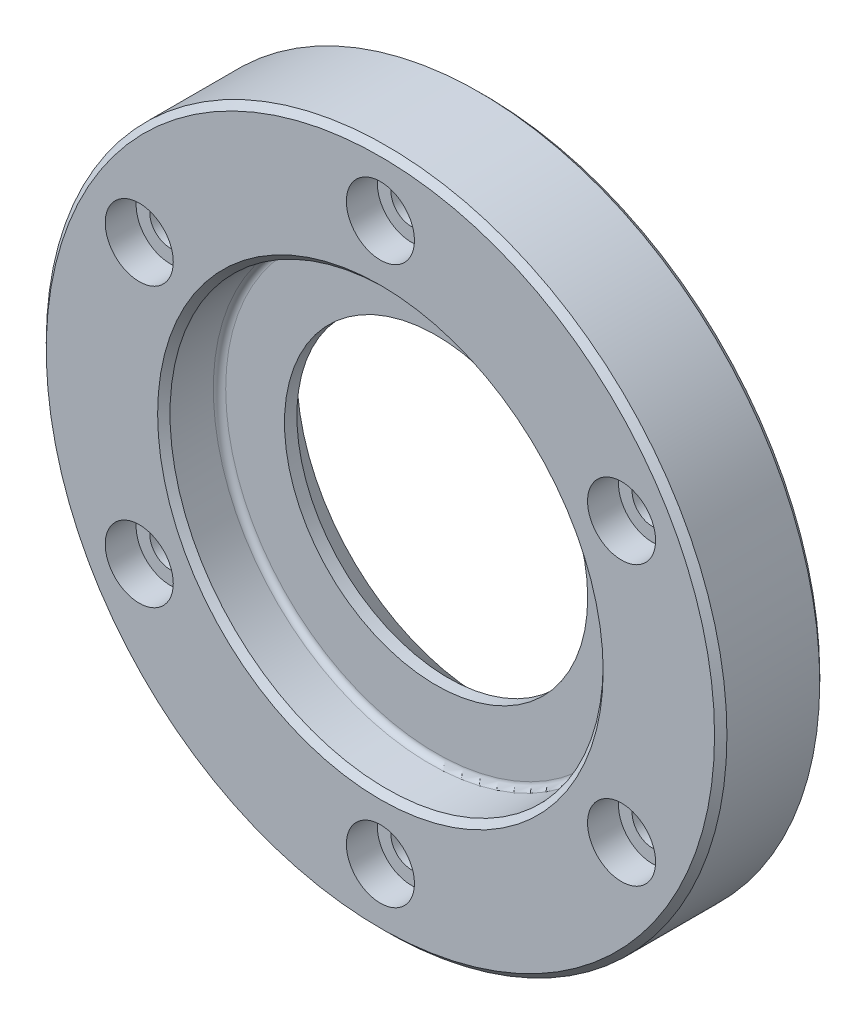
SolidWorks part; units mm, degrees
ref_plane "Front Plane" through (0, 0, 0) normal (0, 0, 1) x (1, 0, 0)
ref_plane "Top Plane" through (0, 0, 0) normal (0, 1, 0) x (1, 0, 0)
ref_plane "Right Plane" through (0, 0, 0) normal (1, 0, 0) x (0, 0, -1)
sketch "Sketch1" plane through (0, 0, 0) normal (1, 0, 0) x (0, 0, -1)
  line L0 (9, 24.5) -> (11, 24.5)
  line L1 (17, 30.5) -> (17, 54)
  line L2 (16, 55) -> (1, 55)
  line L3 (0, 54) -> (0, 36)
  line L4 (1, 35) -> (8, 35)
  line L5 (9, 34) -> (9, 24.5)
  line L6 (11, 24.5) -> (17, 30.5)
  line L7 (0, 0) -> (42.912, 0) construction
  line L8 (17, 54) -> (16, 55)
  line L9 (1, 55) -> (0, 54)
  line L10 (0, 36) -> (1, 35)
  arc A0 (8, 35) -> (9, 34) centre (8, 34) cw
  point P1 (17, 24.5)
  point P3 (17, 55)
  point P4 (0, 55)
  point P5 (0, 35)
  point P19 (9, 35)
  dimension "D7" = 1
  dimension "D1" = 17
  dimension "D2" = 24.5
  dimension "D3" = 30.5
  dimension "D4" = 10.5
  dimension "D5" = 9
  dimension "D6" = 17
revolve "Revolve1" add sketch "Sketch1" angle 360 about L7
sketch "Sketch2" plane through (0, 0, 0) normal (0, 0, 1) x (1, 0, 0)
  point P0 (0, 45)
  dimension "D1" = 45
hole_wizard "CBORE for M6 Hex Socket Head Cap Screw1" positions "Sketch2" profile "Sketch3" counterbore size "M6" standard "ISO" end condition up to next
sketch "Sketch3" plane through (0, 45, 0) normal (1, 0, 0) x (0, -1, 0)
  line L0 (0, 0) -> (0, 17)
  line L1 (0, 17) -> (3.3, 17)
  line L3 (3.3, 17) -> (3.3, 5)
  line L4 (3.3, 5) -> (5.5, 5)
  line L5 (5.5, 5) -> (5.5, 0)
  line L7 (5.5, 0) -> (0, 0)
  line L11 (0, -6.35) -> (0, 107.95) construction
  dimension "Thru Hole Dia." = 6.6
  dimension "Thru Hole Depth" = 17
  dimension "C'Bore Dia." = 11
  dimension "C'Bore Depth" = 5
pattern_circular "CirPattern1" count 6 over 360 about axis through (0, 0, 0) along (0, 0, 1) of "CBORE for M6 Hex Socket Head Cap Screw1"
